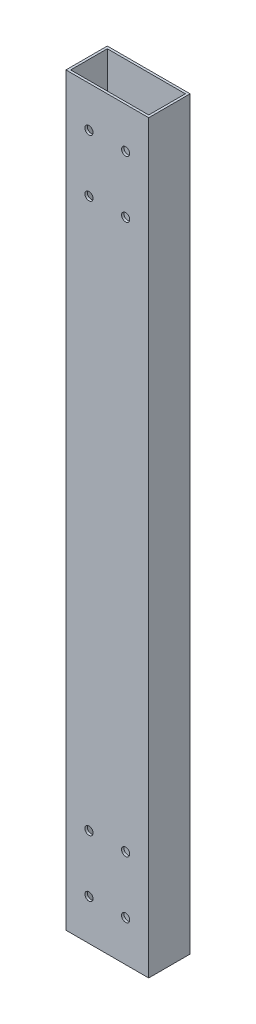
SolidWorks part; units mm, degrees
material "Thornel VCB-20 Carbon Cloth"
ref_plane "Front Plane" through (0, 0, 0) normal (0, 0, 1) x (1, 0, 0)
ref_plane "Top Plane" through (0, 0, 0) normal (0, 1, 0) x (1, 0, 0)
ref_plane "Right Plane" through (0, 0, 0) normal (1, 0, 0) x (0, 0, -1)
sketch "Sketch1" plane through (0, 0, 0) normal (0, 1, 0) x (1, 0, 0)
  line L0 (-25.4, 0) -> (-28.575, 0) construction
  line L1 (-25.4, -12.7) -> (25.4, -12.7)
  line L2 (-25.4, -12.7) -> (-25.4, 12.7)
  line L3 (-25.4, 12.7) -> (25.4, 12.7)
  line L4 (25.4, -12.7) -> (25.4, 12.7)
  line L5 (-25.4, -12.7) -> (25.4, 12.7) construction
  line L6 (-25.4, 12.7) -> (25.4, -12.7) construction
  line L11 (-23.95, 11.25) -> (23.95, 11.25)
  line L12 (23.95, -11.25) -> (23.95, 11.25)
  line L13 (0, -12.7) -> (0, -15.875) construction
  line L14 (-23.95, -11.25) -> (23.95, -11.25)
  line L15 (-23.95, -11.25) -> (-23.95, 11.25)
  point P0 (0, 0)
  point P6 (0, 0)
  dimension "D1" = 25.4
  dimension "D2" = 50.8
  dimension "D3" = 1.45
extrude "Boss-Extrude1" add sketch "Sketch1" along normal blind 457.2
sketch "Sketch2" plane through (0, 0, 12.7) normal (0, 0, 1) x (1, 0, 0)
  line L1 (-11.25, 25) -> (11.25, 25) construction
  line L2 (-11.25, 25) -> (-11.25, 60) construction
  line L3 (-11.25, 60) -> (11.25, 60) construction
  line L4 (11.25, 25) -> (11.25, 60) construction
  circle A0 centre (-11.25, 60) radius 2.5
  circle A1 centre (-11.25, 25) radius 2.5
  circle A2 centre (11.25, 25) radius 2.5
  circle A3 centre (11.25, 60) radius 2.5
  point P4 (0, 25)
  dimension "D4" = 5
  dimension "D1" = 22.5
  dimension "D2" = 35
  dimension "D3" = 25
extrude "Cut-Extrude1" cut sketch "Sketch2" against normal through all contours A3 | A0 | A1 | A2
ref_plane "Plane1" through (0, 228.6, 0) normal (0, 1, 0) x (1, 0, 0)
mirror "Mirror1" about plane through (0, 228.6, 0) normal (0, 1, 0) of "Cut-Extrude1"
equation "\"tube_width\"= 1in"
equation "\"tube_height\"= 2in"
equation "\"tube_thickness\"= 0.125in"
equation "\"tube_length\"= 1.5ft"
equation "\"D1@Boss-Extrude1\"=\"tube_length\""
equation "\"D1@Sketch1\"=\"tube_width\""
equation "\"D2@Sketch1\"=\"tube_height\""
